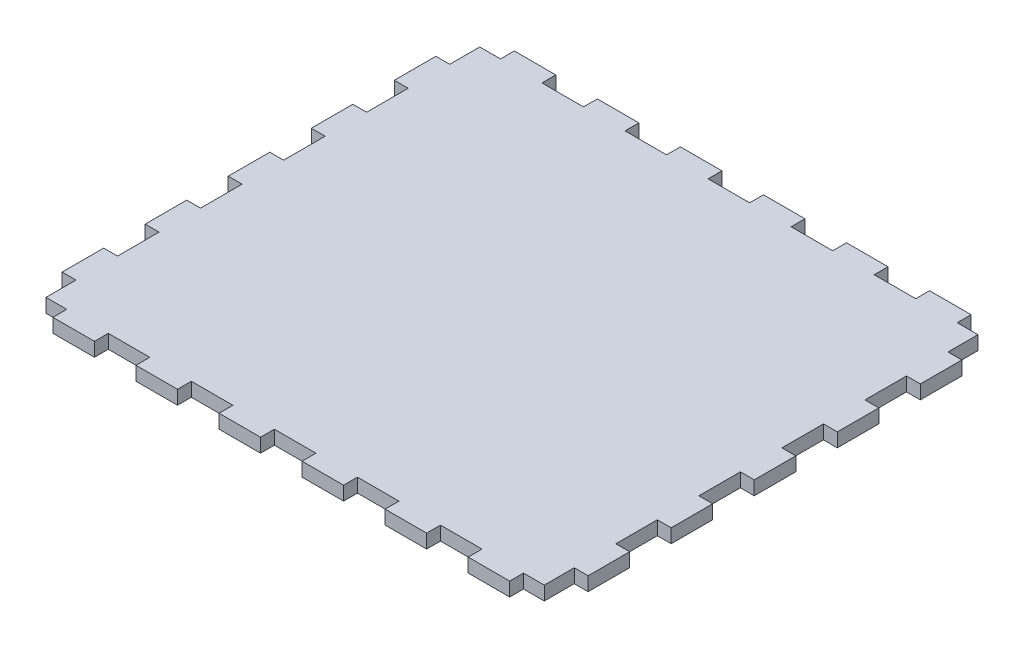
SolidWorks part; units mm, degrees
ref_plane "Front Plane" through (0, 0, 0) normal (0, 0, 1) x (1, 0, 0)
ref_plane "Top Plane" through (0, 0, 0) normal (0, 1, 0) x (1, 0, 0)
ref_plane "Right Plane" through (0, 0, 0) normal (1, 0, 0) x (0, 0, -1)
sketch "Sketch1" plane through (0, 0, 0) normal (0, 1, 0) x (1, 0, 0)
  line L92 (49.5, 50) -> (40.5, 50)
  line L93 (40.5, 50) -> (40.5, 47)
  line L94 (40.5, 47) -> (31.5, 47)
  line L95 (31.5, 47) -> (31.5, 50)
  line L96 (31.5, 50) -> (22.5, 50)
  line L97 (22.5, 50) -> (22.5, 47)
  line L98 (22.5, 47) -> (13.5, 47)
  line L99 (13.5, 47) -> (13.5, 50)
  line L100 (13.5, 50) -> (4.5, 50)
  line L101 (4.5, 50) -> (4.5, 47)
  line L102 (4.5, 47) -> (-4.5, 47)
  line L103 (-4.5, 47) -> (-4.5, 50)
  line L104 (-4.5, 50) -> (-13.5, 50)
  line L105 (-13.5, 50) -> (-13.5, 47)
  line L106 (-13.5, 47) -> (-22.5, 47)
  line L107 (-22.5, 47) -> (-22.5, 50)
  line L108 (-22.5, 50) -> (-31.5, 50)
  line L109 (-31.5, 50) -> (-31.5, 47)
  line L110 (-31.5, 47) -> (-40.5, 47)
  line L111 (-40.5, 47) -> (-40.5, 50)
  line L112 (-40.5, 50) -> (-49.5, 50)
  line L113 (-49.5, 50) -> (-49.5, 47)
  line L114 (-49.5, 47) -> (-54, 47)
  line L115 (-54, 47) -> (-54, 40.5)
  line L116 (-54, 40.5) -> (-57, 40.5)
  line L117 (-57, 40.5) -> (-57, 31.5)
  line L118 (-57, 31.5) -> (-54, 31.5)
  line L119 (-54, 31.5) -> (-54, 22.5)
  line L120 (-54, 22.5) -> (-57, 22.5)
  line L121 (-57, 22.5) -> (-57, 13.5)
  line L122 (-57, 13.5) -> (-54, 13.5)
  line L123 (-54, 13.5) -> (-54, 4.5)
  line L124 (-54, 4.5) -> (-57, 4.5)
  line L125 (-57, 4.5) -> (-57, -4.5)
  line L126 (-57, -4.5) -> (-54, -4.5)
  line L127 (-54, -4.5) -> (-54, -13.5)
  line L128 (-54, -13.5) -> (-57, -13.5)
  line L129 (-57, -13.5) -> (-57, -22.5)
  line L130 (-57, -22.5) -> (-54, -22.5)
  line L131 (-54, -22.5) -> (-54, -31.5)
  line L132 (-54, -31.5) -> (-57, -31.5)
  line L133 (-57, -31.5) -> (-57, -40.5)
  line L134 (-57, -40.5) -> (-54, -40.5)
  line L135 (-54, -40.5) -> (-54, -47)
  line L136 (-54, -47) -> (-49.5, -47)
  line L137 (-49.5, -47) -> (-49.5, -50)
  line L138 (-49.5, -50) -> (-40.5, -50)
  line L139 (-40.5, -50) -> (-40.5, -47)
  line L140 (-40.5, -47) -> (-31.5, -47)
  line L141 (-31.5, -47) -> (-31.5, -50)
  line L142 (-31.5, -50) -> (-22.5, -50)
  line L143 (-22.5, -50) -> (-22.5, -47)
  line L144 (-22.5, -47) -> (-13.5, -47)
  line L145 (-13.5, -47) -> (-13.5, -50)
  line L146 (-13.5, -50) -> (-4.5, -50)
  line L147 (-4.5, -50) -> (-4.5, -47)
  line L148 (-4.5, -47) -> (4.5, -47)
  line L149 (4.5, -47) -> (4.5, -50)
  line L150 (4.5, -50) -> (13.5, -50)
  line L151 (13.5, -50) -> (13.5, -47)
  line L152 (13.5, -47) -> (22.5, -47)
  line L153 (22.5, -47) -> (22.5, -50)
  line L154 (22.5, -50) -> (31.5, -50)
  line L155 (31.5, -50) -> (31.5, -47)
  line L156 (31.5, -47) -> (40.5, -47)
  line L157 (40.5, -47) -> (40.5, -50)
  line L158 (40.5, -50) -> (49.5, -50)
  line L159 (49.5, -50) -> (49.5, -47)
  line L160 (49.5, -47) -> (54, -47)
  line L161 (54, -47) -> (54, -40.5)
  line L162 (54, -40.5) -> (57, -40.5)
  line L163 (57, -40.5) -> (57, -31.5)
  line L164 (57, -31.5) -> (54, -31.5)
  line L165 (54, -31.5) -> (54, -22.5)
  line L166 (54, -22.5) -> (57, -22.5)
  line L167 (57, -22.5) -> (57, -13.5)
  line L168 (57, -13.5) -> (54, -13.5)
  line L169 (54, -13.5) -> (54, -4.5)
  line L170 (54, -4.5) -> (57, -4.5)
  line L171 (57, -4.5) -> (57, 4.5)
  line L172 (57, 4.5) -> (54, 4.5)
  line L173 (54, 4.5) -> (54, 13.5)
  line L174 (54, 13.5) -> (57, 13.5)
  line L175 (57, 13.5) -> (57, 22.5)
  line L176 (57, 22.5) -> (54, 22.5)
  line L177 (54, 22.5) -> (54, 31.5)
  line L178 (54, 31.5) -> (57, 31.5)
  line L179 (57, 31.5) -> (57, 40.5)
  line L180 (57, 40.5) -> (54, 40.5)
  line L181 (54, 40.5) -> (54, 47)
  line L182 (54, 47) -> (49.5, 47)
  line L183 (49.5, 47) -> (49.5, 50)
  line L184 (-57, 40.5) -> (-57, 50) construction
  line L185 (-57, 50) -> (-49.5, 50) construction
  line L186 (57, -40.5) -> (57, -50) construction
  line L187 (57, -50) -> (49.5, -50) construction
  line L188 (-57, 50) -> (57, -50) construction
  point P0 (0, 0)
extrude "Boss-Extrude1" add sketch "Sketch1" along normal mid plane 3
sketch "Sketch2" plane through (0, 1.5, 0) normal (0, 1, 0) x (1, 0, 0)
  text T0 "Top/Bottom"
extrude "Cut-Extrude1" [suppressed] cut sketch "Sketch2" against normal blind 1
sketch "Sketch3" plane through (0, 1.5, 0) normal (0, 1, 0) x (1, 0, 0)
  line L0 (-60, 30.5) -> (61, 30.5) construction
  line L1 (-40.5, 47) -> (-40.5, 50) construction
  line L2 (-54, 40.5) -> (-57, 40.5) construction
  line L3 (54, 31.5) -> (57, 31.5) construction
  point P0 (-60, 30.5)
  point P1 (61, 30.5)
  dimension "D1" = 19.5
  dimension "D2" = 10
  dimension "D3" = 1
hole_wizard "Ø6.2 (6.2) Diameter Hole1" [suppressed] positions "Sketch3" profile "Sketch4" hole size "Ø6.2" standard "ISO"
sketch "Sketch4" plane through (-50, 1.5, -30.5) normal (1, 0, 0) x (0, 0, 1)
  line L0 (0, 0) -> (0, 3)
  line L1 (0, 3) -> (3.1, 3)
  line L2 (3.1, 3) -> (3.1, 0.025)
  line L3 (3.1, 0.025) -> (3.125, 0)
  line L5 (3.125, 0) -> (0, 0)
  line L6 (-3.1, 0.025) -> (-3.125, 0) construction
  line L11 (0, -6.35) -> (0, 107.95) construction
  dimension "Thru Hole Dia." = 6.2
  dimension "Thru Hole Depth" = 3
  dimension "Near C'Sink Dia." = 6.25
  dimension "Near C'Sink Angle" = 90
